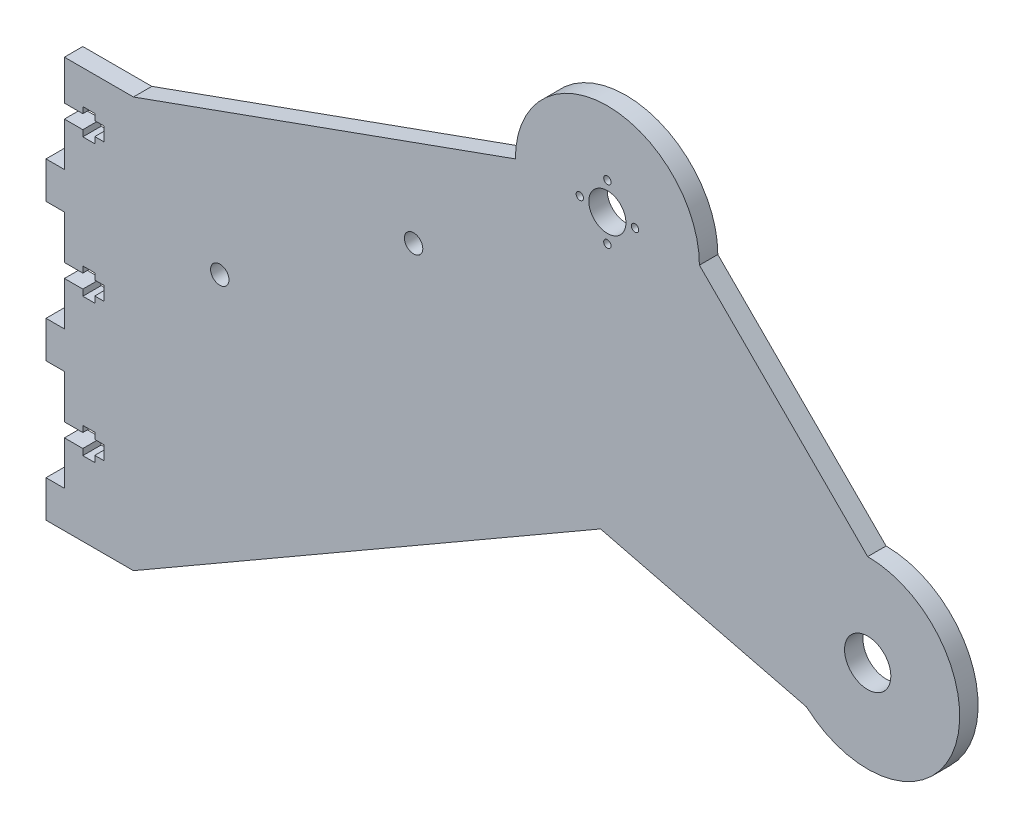
SolidWorks part; units mm, degrees
ref_plane "前视基准面" through (0, 0, 0) normal (0, 0, 1) x (1, 0, 0)
ref_plane "上视基准面" through (0, 0, 0) normal (0, 1, 0) x (1, 0, 0)
ref_plane "右视基准面" through (0, 0, 0) normal (1, 0, 0) x (0, 0, -1)
sketch "草图1" plane through (0, 0, 0) normal (0, 0, 1) x (1, 0, 0)
  line L0 (-1.7171, -22.1136) -> (2.2829, -22.1136)
  line L1 (2.2829, -22.1136) -> (2.2829, -23.4636)
  line L2 (2.2829, -23.4636) -> (4.8829, -23.4636)
  line L3 (4.8829, -23.4636) -> (4.8829, -22.1136)
  line L4 (4.8829, -22.1136) -> (6.8829, -22.1136)
  line L5 (6.8829, -22.1136) -> (6.8829, -19.1136)
  line L6 (-1.7171, -20.6136) -> (-3.0249, -20.6136) construction
  line L7 (-1.7171, -22.1136) -> (-1.7171, -19.1136) construction
  line L8 (4.8829, -17.7636) -> (4.8829, -19.1136)
  line L9 (2.2829, -19.1136) -> (2.2829, -17.7636)
  line L10 (4.8829, -19.1136) -> (6.8829, -19.1136)
  line L11 (2.2829, -17.7636) -> (4.8829, -17.7636)
  line L12 (-1.7171, -19.1136) -> (2.2829, -19.1136)
  line L13 (-1.7171, -39.6136) -> (-5.7171, -39.6136)
  line L14 (-5.7171, -39.6136) -> (-5.7171, -31.6136)
  line L15 (-5.7171, -31.6136) -> (-1.7171, -31.6136)
  line L16 (-1.7171, -31.6136) -> (-1.7171, -22.1136)
  line L17 (-5.7171, -35.6136) -> (-4.0142, -35.6136) construction
  line L18 (6.8829, 39.3864) -> (3.9614, 39.3864) construction
  line L19 (-5.7171, 24.3864) -> (-4.0142, 24.3864) construction
  line L20 (6.8829, 9.3864) -> (3.9614, 9.3864) construction
  line L21 (-5.7171, -5.6136) -> (-4.0142, -5.6136) construction
  line L22 (-1.7171, -22.1136) -> (2.2829, -22.1136)
  line L23 (2.2829, -22.1136) -> (2.2829, -23.4636)
  line L24 (2.2829, -23.4636) -> (4.8829, -23.4636)
  line L25 (4.8829, -23.4636) -> (4.8829, -22.1136)
  line L26 (4.8829, -22.1136) -> (6.8829, -22.1136)
  line L27 (4.8829, -17.7636) -> (4.8829, -19.1136)
  line L28 (2.2829, -19.1136) -> (2.2829, -17.7636)
  line L29 (4.8829, -19.1136) -> (6.8829, -19.1136)
  line L30 (-1.7171, -22.1136) -> (2.2829, -22.1136)
  line L31 (2.2829, -23.4636) -> (4.8829, -23.4636)
  line L32 (4.8829, -22.1136) -> (6.8829, -22.1136)
  line L33 (2.2829, -22.1136) -> (2.2829, -23.4636)
  line L34 (4.8829, -23.4636) -> (4.8829, -22.1136)
  line L35 (4.8829, -19.1136) -> (6.8829, -19.1136)
  line L36 (4.8829, -17.7636) -> (4.8829, -19.1136)
  line L37 (2.2829, -17.7636) -> (4.8829, -17.7636)
  line L38 (2.2829, -19.1136) -> (2.2829, -17.7636)
  line L39 (-1.7171, -19.1136) -> (2.2829, -19.1136)
  line L40 (2.2829, -17.7636) -> (4.8829, -17.7636)
  line L41 (-1.7171, -19.1136) -> (2.2829, -19.1136)
  line L42 (2.2829, 36.5364) -> (4.8829, 36.5364)
  line L43 (4.8829, 37.8864) -> (6.8829, 37.8864)
  line L44 (2.2829, 37.8864) -> (2.2829, 36.5364)
  line L45 (4.8829, 36.5364) -> (4.8829, 37.8864)
  line L46 (6.8829, 40.8864) -> (6.8829, 37.8864)
  line L47 (4.8829, 40.8864) -> (6.8829, 40.8864)
  line L48 (4.8829, 42.2364) -> (4.8829, 40.8864)
  line L49 (2.2829, 42.2364) -> (4.8829, 42.2364)
  line L50 (2.2829, 40.8864) -> (2.2829, 42.2364)
  line L51 (2.2829, 40.8864) -> (-1.7171, 40.8864)
  line L52 (2.2829, 37.8864) -> (-1.7171, 37.8864)
  line L53 (-1.7171, 28.3864) -> (-1.7171, 37.8864)
  line L54 (-1.7171, 20.3864) -> (-5.7171, 20.3864)
  line L55 (-5.7171, 20.3864) -> (-5.7171, 28.3864)
  line L56 (-5.7171, 28.3864) -> (-1.7171, 28.3864)
  line L57 (-1.7171, 7.8864) -> (-1.7171, -1.6136)
  line L58 (2.2829, 7.8864) -> (-1.7171, 7.8864)
  line L59 (2.2829, 10.8864) -> (-1.7171, 10.8864)
  line L60 (-1.7171, 20.3864) -> (-1.7171, 10.8864)
  line L61 (2.2829, 7.8864) -> (2.2829, 6.5364)
  line L62 (2.2829, 6.5364) -> (4.8829, 6.5364)
  line L63 (4.8829, 6.5364) -> (4.8829, 7.8864)
  line L64 (4.8829, 7.8864) -> (6.8829, 7.8864)
  line L65 (6.8829, 7.8864) -> (6.8829, 10.8864)
  line L66 (4.8829, 12.2364) -> (4.8829, 10.8864)
  line L67 (2.2829, 10.8864) -> (2.2829, 12.2364)
  line L68 (4.8829, 10.8864) -> (6.8829, 10.8864)
  line L69 (2.2829, 12.2364) -> (4.8829, 12.2364)
  line L70 (-1.7171, -9.6136) -> (-1.7171, -19.1136)
  line L71 (-5.7171, -9.6136) -> (-1.7171, -9.6136)
  line L72 (-5.7171, -1.6136) -> (-5.7171, -9.6136)
  line L73 (-1.7171, -1.6136) -> (-5.7171, -1.6136)
  line L74 (-1.7171, -22.1136) -> (2.2829, -22.1136)
  line L75 (2.2829, -23.4636) -> (4.8829, -23.4636)
  line L76 (4.8829, -22.1136) -> (6.8829, -22.1136)
  line L77 (2.2829, -22.1136) -> (2.2829, -23.4636)
  line L78 (4.8829, -23.4636) -> (4.8829, -22.1136)
  line L79 (4.8829, -19.1136) -> (6.8829, -19.1136)
  line L80 (4.8829, -17.7636) -> (4.8829, -19.1136)
  line L81 (2.2829, -17.7636) -> (4.8829, -17.7636)
  line L82 (2.2829, -19.1136) -> (2.2829, -17.7636)
  line L83 (-1.7171, -19.1136) -> (2.2829, -19.1136)
  line L84 (-1.7171, 40.8864) -> (-1.7171, 49.5381)
  line L85 (6.8829, -22.1136) -> (13.2829, -22.1136) construction
  line L86 (13.2829, -39.6136) -> (13.2829, 49.5381) construction
  line L87 (17.782, 3.3927) -> (13.2829, -39.6136) construction
  line L88 (116.2829, 79.3864) -> (6.8829, 9.3864) construction
  line L89 (13.2829, -39.6136) -> (-1.7171, -39.6136)
  line L90 (15.6092, 36.7813) -> (13.2829, 49.5381) construction
  line L91 (116.2829, 28.2764) -> (116.2829, 79.3864) construction
  line L92 (116.2829, 70.8864) -> (22.338, 10.7755) construction
  line L93 (107.7829, 79.3864) -> (15.6092, 36.7813) construction
  line L94 (13.2829, 49.5381) -> (-1.7171, 49.5381)
  line L95 (17.782, 3.3927) -> (22.338, 10.7755) construction
  line L96 (13.2829, 49.5381) -> (96.2829, 79.3864)
  line L97 (116.2829, 79.3864) -> (172.8514, 22.8179) construction
  line L98 (159.5453, 7.8864) -> (114.7958, 18.995)
  line L99 (172.8514, 42.8179) -> (136.2829, 79.3864)
  line L100 (114.7958, 18.995) -> (13.2829, -39.6136)
  circle A3 centre (116.2829, 79.3864) radius 8.5 construction
  circle A5 centre (116.2829, 73.3864) radius 0.8
  circle A6 centre (172.8514, 22.8179) radius 5.03
  circle A7 centre (116.2829, 79.3864) radius 4.03
  circle A8 centre (172.8514, 22.8179) radius 20 construction
  circle A9 centre (74.1665, 52.4381) radius 2
  circle A10 centre (32.0501, 25.4898) radius 2
  circle A11 centre (116.2829, 79.3864) radius 20 construction
  arc A12 (159.5453, 7.8864) -> (172.8514, 42.8179) centre (172.8514, 22.8179) ccw
  arc A13 (136.2829, 79.3864) -> (96.2829, 79.3864) centre (116.2829, 79.3864) ccw
  circle A14 centre (110.2829, 79.3864) radius 0.8
  circle A15 centre (116.2829, 85.3864) radius 0.8
  circle A16 centre (122.2829, 79.3864) radius 0.8
  point P11 (-2.371, -20.6136)
  dimension "D8" = 4
  dimension "D9" = 118
  dimension "D12" = 80
  dimension "D13" = 45
  dimension "D14" = 50
  dimension "D16" = 10.06
  dimension "D18" = 8.06
  dimension "D1" = 4
  dimension "D2" = 2
  dimension "D3" = 2.6
  dimension "D4" = 1.35
  dimension "D5" = 1.5
  dimension "D6" = 9.5
  dimension "D7" = 15
  dimension "D10" = 6
  dimension "D11" = 40
  dimension "D15" = 50
  dimension "D17" = 60
extrude "凸台-拉伸1" add sketch "草图1" along normal blind 4
sketch "草图2" plane through (-1.7171, 0, 0) normal (-1, 0, 0) x (0, 0, 1)
  line L0 (2, -19.1136) -> (2, -22.1136)
  line L1 (4, -19.1136) -> (0, -19.1136) construction
  line L2 (4, -22.1136) -> (0, -22.1136) construction
  circle A0 centre (2, -20.6136) radius 1.5
